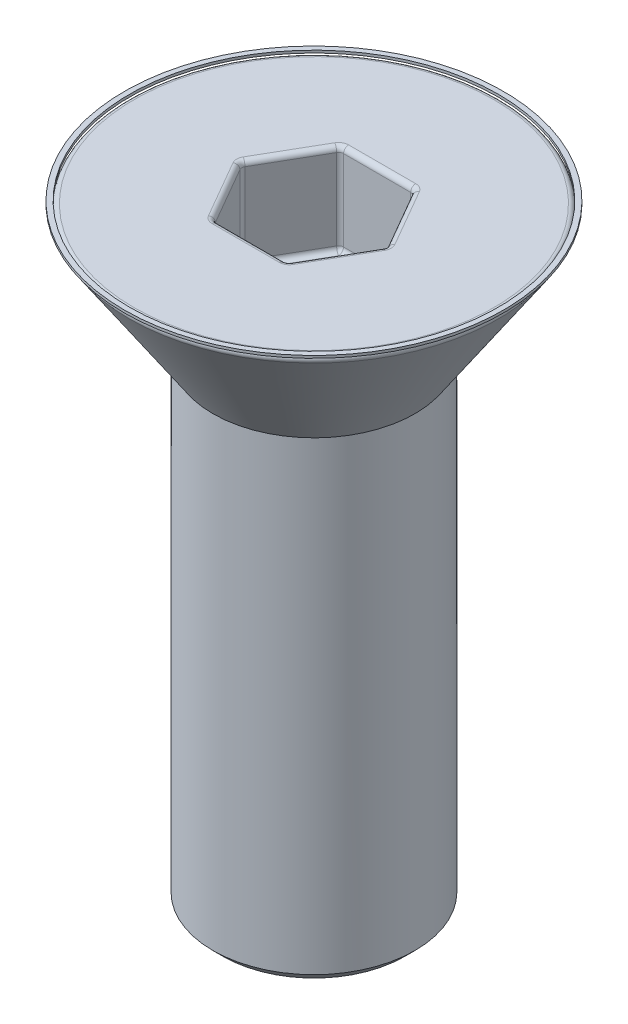
SolidWorks part; units mm, degrees
material "AISI 304"
ref_plane "前视基准面" through (0, 0, 0) normal (0, 0, 1) x (1, 0, 0)
ref_plane "上视基准面" through (0, 0, 0) normal (0, 1, 0) x (1, 0, 0)
ref_plane "右视基准面" through (0, 0, 0) normal (1, 0, 0) x (0, 0, -1)
sketch "Sketch1" plane through (0, 0, 0) normal (1, 0, 0) x (0, 0, -1)
  line L0 (0, 2.6) -> (0, -9.4) construction
  line L1 (3.75, 2.6) -> (-3.75, 2.6) construction
  line L2 (-3.75, 2.6) -> (-2, 0)
  line L3 (-2, 0) -> (-2, -9.4)
  line L4 (-2, -9.4) -> (2, -9.4) construction
  line L5 (2, 0) -> (2, -9.4) construction
  line L6 (3.75, 2.6) -> (2, 0) construction
  line L7 (-3.75, 2.6) -> (0, 2.6)
  line L8 (0, 2.6) -> (0, -9.4)
  line L9 (0, -9.4) -> (-2, -9.4)
  dimension "公称直径" = 4
  dimension "螺丝长度" = 12
  dimension "头部厚度" = 2.6
  dimension "头部直径" = 7.5
revolve "Revolve1" add sketch "Sketch1" angle 360 about L8
sketch "Sketch2" plane through (0, 2.6, 0) normal (0, 1, 0) x (1, 0, 0)
  line L1 (1.4434, 0) -> (0.7217, 1.25)
  line L2 (0.7217, 1.25) -> (-0.7217, 1.25)
  line L3 (-0.7217, 1.25) -> (-1.4434, 0)
  line L4 (-1.4434, 0) -> (-0.7217, -1.25)
  line L5 (-0.7217, -1.25) -> (0.7217, -1.25)
  line L6 (0.7217, -1.25) -> (1.4434, 0)
  circle A0 centre (0, 0) radius 1.25 construction
  dimension "六角对边" = 2.5
extrude "Cut-Extrude1" cut sketch "Sketch2" against normal blind 1.8
chamfer "Chamfer1" distance 0.2 angle 45 1 edges at (0, -9.4, 2)
fillet "Fillet1" radius 0.1 19 edges at (-1.0825, 0.8, 0.625) (-1.0825, 2.6, 0.625) (-0.7217, 1.7, 1.25) (0, 0.8, 1.25) (0, 2.6, 1.25) (0.7217, 1.7, 1.25) (1.0825, 0.8, 0.625) (1.0825, 2.6, 0.625) (1.4434, 1.7, 0) (1.0825, 0.8, -0.625) (1.0825, 2.6, -0.625) (-1.0825, 0.8, -0.625) (-1.4434, 1.7, 0) (-1.0825, 2.6, -0.625) (0.7217, 1.7, -1.25) (0, 0.8, -1.25) (-0.7217, 1.7, -1.25) (0, 2.6, -1.25) (0, 2.6, 3.75)
sketch "草图1" plane through (0, 2.6, 0) normal (0, 1, 0) x (1, 0, 0)
  circle A0 centre (0, 0) radius 3.65
  circle A1 centre (0, 0) radius 3.75
  dimension "D1" = 0.1
extrude "参考配合凸台" add sketch "草图1" along normal blind 0.05 separate body
other "冻结***"
